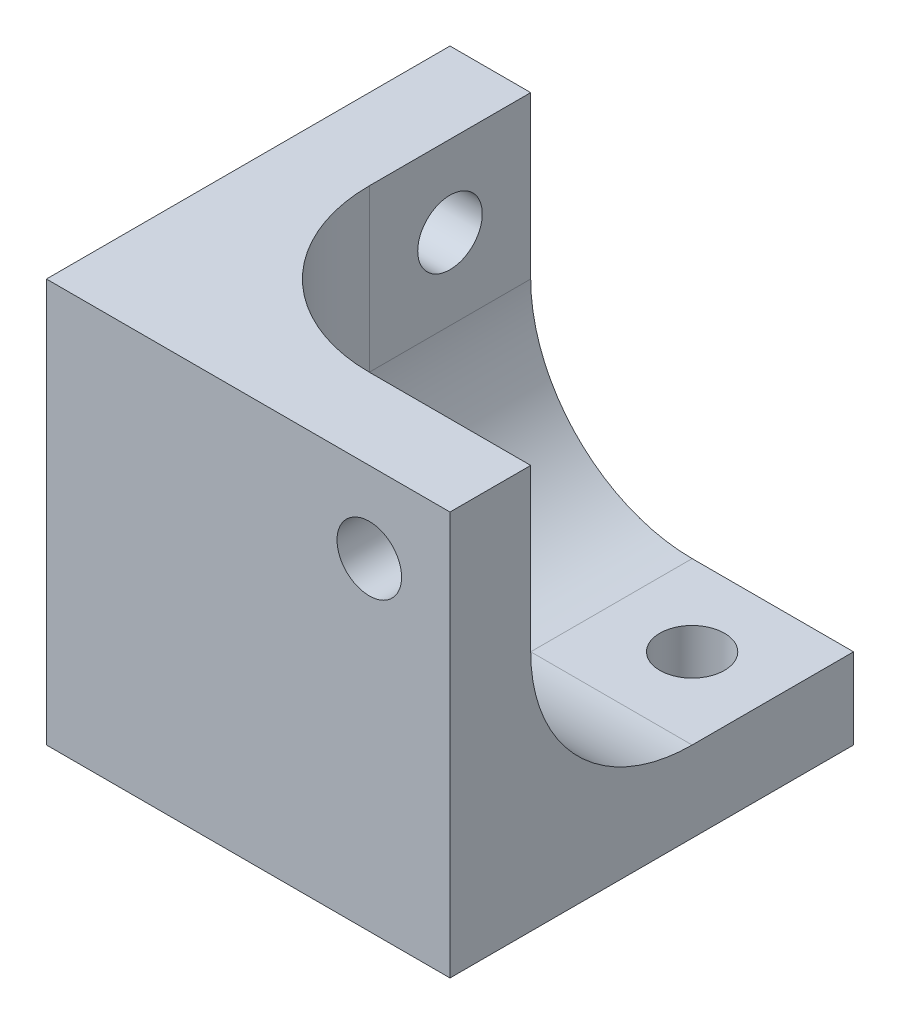
SolidWorks part; units mm, degrees
ref_plane "Front Plane" through (0, 0, 0) normal (0, 0, 1) x (1, 0, 0)
ref_plane "Top Plane" through (0, 0, 0) normal (0, 1, 0) x (1, 0, 0)
ref_plane "Right Plane" through (0, 0, 0) normal (1, 0, 0) x (0, 0, -1)
sketch "Sketch1" plane through (0, 0, 0) normal (0, 1, 0) x (1, 0, 0)
  line L1 (0, 0) -> (50, 0)
  line L2 (0, 0) -> (0, 50)
  line L3 (0, 50) -> (50, 50)
  line L4 (50, 0) -> (50, 50)
  dimension "D1" = 50
  dimension "D2" = 50
extrude "Boss-Extrude1" add sketch "Sketch1" along normal blind 50
sketch "Sketch3" plane through (0, 50, 0) normal (0, 1, 0) x (1, 0, 0)
  line L1 (50, 50) -> (10, 50)
  line L2 (50, 50) -> (50, 10)
  line L3 (50, 10) -> (10, 10)
  line L4 (10, 50) -> (10, 10)
  dimension "D1" = 40
  dimension "D2" = 40
extrude "Cut-Extrude1" cut sketch "Sketch3" against normal blind 40
sketch "Sketch4" plane through (0, 10, 0) normal (0, 1, 0) x (1, 0, 0)
  line L0 (50, 10) -> (50, 50) construction
  line L2 (50, 50) -> (10, 50) construction
  circle A0 centre (40, 40) radius 4
  point P6 (42.6965, 50)
  dimension "D1" = 8
  dimension "D2" = 10
  dimension "D3" = 10
extrude "Cut-Extrude2" cut sketch "Sketch4" against normal blind 40
sketch "Sketch5" plane through (0, 0, 0) normal (0, 0, 1) x (1, 0, 0)
  line L0 (50, 50) -> (50, 0) construction
  line L1 (0, 50) -> (50, 50) construction
  circle A0 centre (40, 40) radius 4
  dimension "D1" = 8
  dimension "D2" = 10
  dimension "D3" = 10
extrude "Cut-Extrude3" cut sketch "Sketch5" against normal blind 40
sketch "Sketch6" plane through (0, 0, 0) normal (-1, 0, 0) x (0, 0, 1)
  line L0 (-50, 50) -> (0, 50) construction
  line L1 (-50, 50) -> (-50, 0) construction
  circle A0 centre (-40, 40) radius 4
  dimension "D1" = 8
  dimension "D2" = 10
  dimension "D3" = 10
extrude "Cut-Extrude4" cut sketch "Sketch6" against normal blind 40
fillet "Fillet1" radius 20 1 edges at (10, 30, -10)
fillet "Fillet2" radius 20 3 edges at (10, 10, -40) (15.8579, 10, -15.8579) (40, 10, -10)
